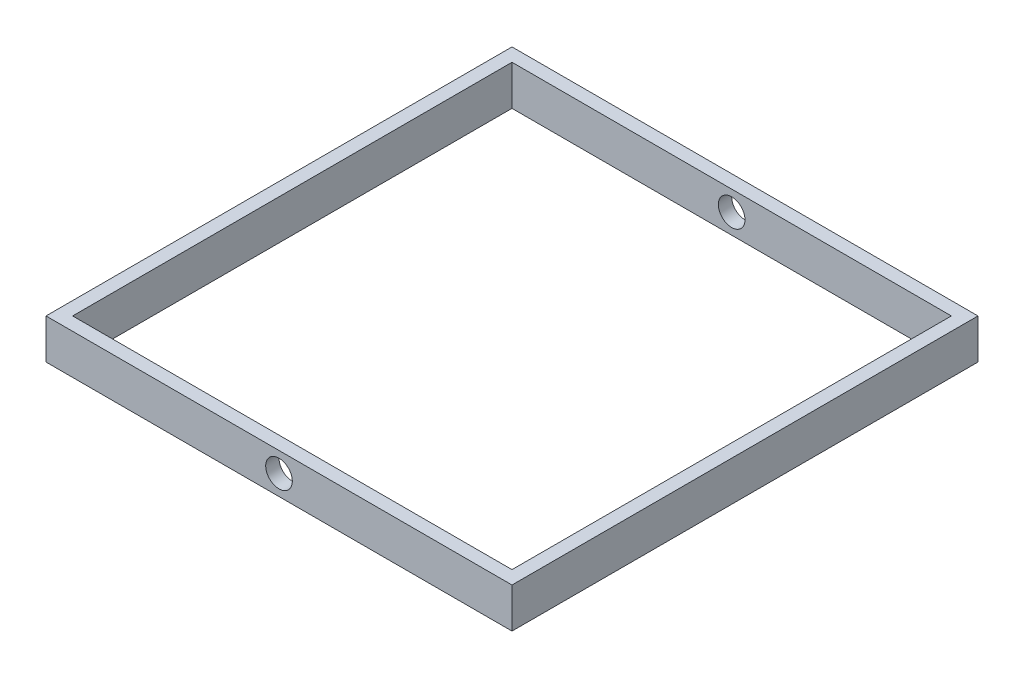
SolidWorks part; units mm, degrees
ref_plane "Front Plane" through (0, 0, 0) normal (0, 0, 1) x (1, 0, 0)
ref_plane "Top Plane" through (0, 0, 0) normal (0, 1, 0) x (1, 0, 0)
ref_plane "Right Plane" through (0, 0, 0) normal (1, 0, 0) x (0, 0, -1)
sketch "Sketch1" plane through (0, 0, 0) normal (0, 1, 0) x (1, 0, 0)
  line L1 (-87.5, -87.5) -> (87.5, -87.5)
  line L2 (-87.5, -87.5) -> (-87.5, 87.5)
  line L3 (-87.5, 87.5) -> (87.5, 87.5)
  line L4 (87.5, -87.5) -> (87.5, 87.5)
  line L5 (-87.5, -87.5) -> (87.5, 87.5) construction
  line L6 (-87.5, 87.5) -> (87.5, -87.5) construction
  point P0 (0, 0)
  dimension "D1" = 175
extrude "Boss-Extrude1" add sketch "Sketch1" along normal blind 15
sketch "Sketch2" plane through (0, 15, 0) normal (0, 1, 0) x (1, 0, 0)
  line L0 (87.5, 87.5) -> (-87.5, 87.5) construction
  line L1 (-82.5, -82.5) -> (82.5, -82.5)
  line L2 (-82.5, -82.5) -> (-82.5, 82.5)
  line L3 (-82.5, 82.5) -> (82.5, 82.5)
  line L4 (82.5, -82.5) -> (82.5, 82.5)
  line L5 (-82.5, -82.5) -> (82.5, 82.5) construction
  line L6 (-82.5, 82.5) -> (82.5, -82.5) construction
  point P1 (0, 0)
  dimension "D1" = 5
extrude "Cut-Extrude1" cut sketch "Sketch2" against normal blind 15
sketch "Sketch3" plane through (0, 0, 87.5) normal (0, 0, 1) x (1, 0, 0)
  line L0 (87.5, 15) -> (87.5, 0) construction
  circle A0 centre (0, 7.5) radius 5
  point P4 (87.5, 7.5)
  point P5 (0, 0)
  dimension "D1" = 10
extrude "Cut-Extrude2" cut sketch "Sketch3" against normal through all
